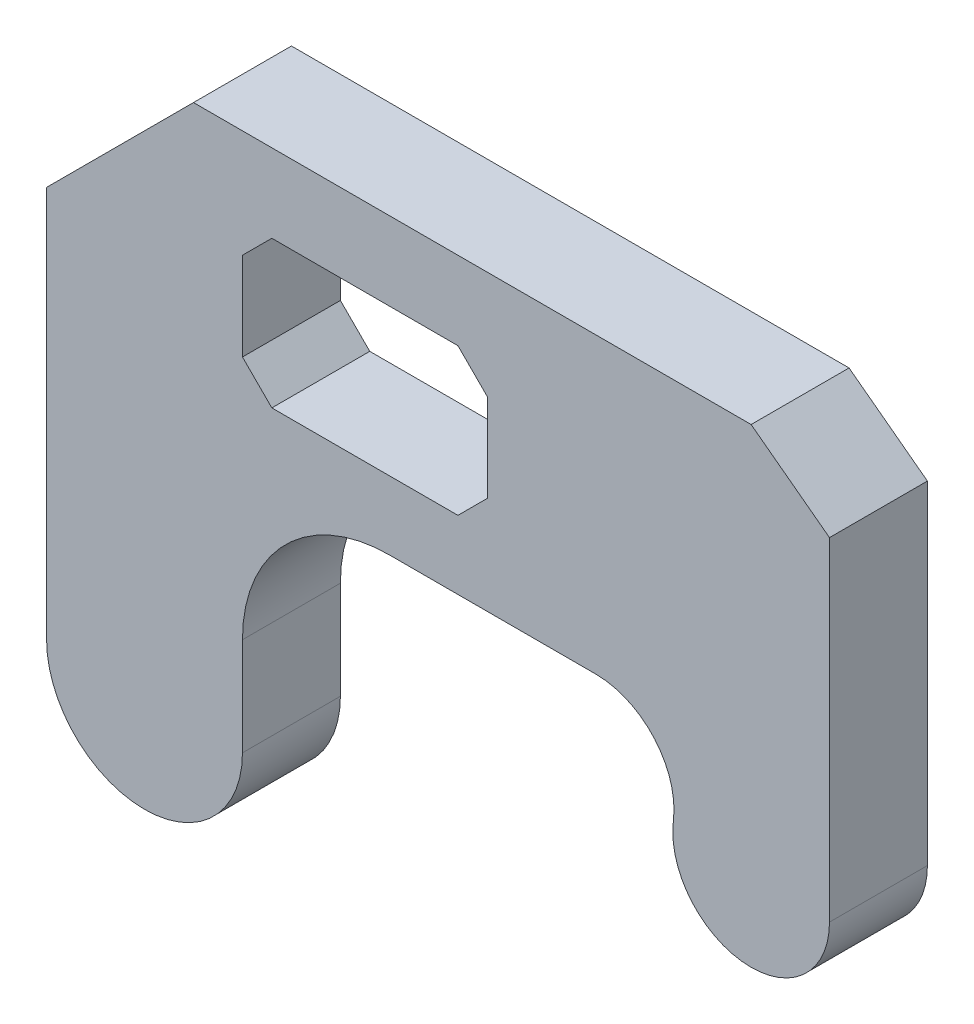
SolidWorks part; units mm, degrees
ref_plane "Alzado" through (0, 0, 0) normal (0, 0, 1) x (1, 0, 0)
ref_plane "Planta" through (0, 0, 0) normal (0, 1, 0) x (1, 0, 0)
ref_plane "Vista lateral" through (0, 0, 0) normal (1, 0, 0) x (0, 0, -1)
sketch "Croquis1" plane through (0, 0, 0) normal (0, 0, 1) x (1, 0, 0)
  line L0 (0, 0) -> (0, 40)
  line L1 (0, 40) -> (15, 55)
  line L2 (15, 55) -> (71.9373, 55)
  line L3 (71.9373, 55) -> (79.9373, 49)
  line L4 (79.9373, 49) -> (79.9373, 15)
  line L5 (56.0627, 25) -> (35, 25)
  line L6 (20, 10) -> (20, 0)
  line L7 (20, 44) -> (23, 47)
  line L8 (23, 47) -> (42, 47)
  line L9 (20, 44) -> (20, 35)
  line L10 (23, 32) -> (42, 32)
  line L11 (45, 44) -> (45, 35)
  line L12 (42, 47) -> (45, 44)
  line L13 (20, 35) -> (23, 32)
  line L14 (42, 32) -> (45, 35)
  arc A0 (79.9373, 15) -> (64, 16) centre (71.9373, 15) cw
  arc A1 (64, 16) -> (56.0627, 25) centre (56.0627, 17) ccw
  arc A2 (35, 25) -> (20, 10) centre (35, 10) ccw
  arc A3 (20, 0) -> (0, 0) centre (10, 0) cw
  point P19 (45.5314, 25)
  point P22 (20, 47)
  point P23 (45, 32)
  point P24 (20, 32)
  point P25 (45, 47)
  dimension "D7" = 10
  dimension "D8" = 15
  dimension "D9" = 8
  dimension "D10" = 8
  dimension "D11" = 8
  dimension "D1" = 15
  dimension "D2" = 55
  dimension "D3" = 15
  dimension "D4" = 25
  dimension "D5" = 40
  dimension "D6" = 6
  dimension "D12" = 44
  dimension "D13" = 20
  dimension "D14" = 8
  dimension "D15" = 25
  dimension "D16" = 15
extrude "Saliente-Extruir1" add sketch "Croquis1" along normal blind 10
